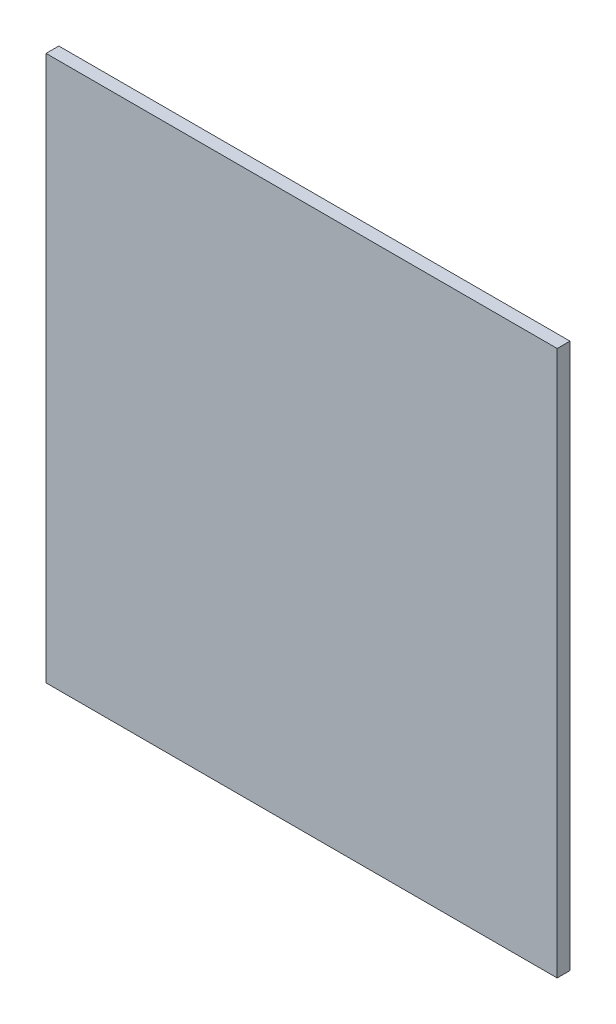
SolidWorks part; units mm, degrees
ref_plane "Alzado" through (0, 0, 0) normal (0, 0, 1) x (1, 0, 0)
ref_plane "Planta" through (0, 0, 0) normal (0, 1, 0) x (1, 0, 0)
ref_plane "Vista lateral" through (0, 0, 0) normal (1, 0, 0) x (0, 0, -1)
sketch "Croquis1" plane through (0, 0, 0) normal (0, 0, 1) x (1, 0, 0)
  line L1 (200, 213.32) -> (-200, 213.32)
  line L2 (200, 213.32) -> (200, -213.32)
  line L3 (200, -213.32) -> (-200, -213.32)
  line L4 (-200, 213.32) -> (-200, -213.32)
  line L5 (200, 213.32) -> (-200, -213.32) construction
  line L6 (200, -213.32) -> (-200, 213.32) construction
  point P0 (0, 0)
  dimension "D1" = 400
  dimension "D2" = 426.64
extrude "Saliente-Extruir1" add sketch "Croquis1" along normal blind 10
sketch "Croquis2" plane through (0, 0, 0) normal (0, 0, -1) x (-1, 0, 0)
  line L0 (-200, -213.32) -> (-200, -183.32)
  line L1 (-200, -213.32) -> (-200, 213.32) construction
  line L2 (-200, -183.32) -> (-170, -183.32)
  line L3 (-200, 213.32) -> (-170, 213.32)
  line L4 (-200, 213.32) -> (200, 213.32) construction
  line L5 (-170, 213.32) -> (-170, 183.32)
  line L6 (200, 213.32) -> (170, 213.32)
  line L7 (170, 213.32) -> (170, 183.32)
  line L8 (200, -213.32) -> (170, -213.32)
  line L9 (200, -213.32) -> (-200, -213.32) construction
  line L10 (170, -213.32) -> (170, -183.32)
  line L12 (-170, 170.6183) -> (-159, 176.9691)
  line L13 (-159, 176.9691) -> (-159, 189.6709)
  line L14 (-159, 189.6709) -> (-170, 196.0217)
  line L15 (-170, 196.0217) -> (-181, 189.6709)
  line L16 (-181, 189.6709) -> (-181, 176.9691)
  line L17 (-181, 176.9691) -> (-170, 170.6183)
  line L18 (-170, -170.6183) -> (-181, -176.9691)
  line L19 (-181, -176.9691) -> (-181, -189.6709)
  line L20 (-181, -189.6709) -> (-170, -196.0217)
  line L21 (-170, -196.0217) -> (-159, -189.6709)
  line L22 (-159, -189.6709) -> (-159, -176.9691)
  line L23 (-159, -176.9691) -> (-170, -170.6183)
  line L24 (170, 170.6183) -> (181, 176.9691)
  line L25 (181, 176.9691) -> (181, 189.6709)
  line L26 (181, 189.6709) -> (170, 196.0217)
  line L27 (170, 196.0217) -> (159, 189.6709)
  line L28 (159, 189.6709) -> (159, 176.9691)
  line L29 (159, 176.9691) -> (170, 170.6183)
  line L30 (170, -170.6183) -> (159, -176.9691)
  line L31 (159, -176.9691) -> (159, -189.6709)
  line L32 (159, -189.6709) -> (170, -196.0217)
  line L33 (170, -196.0217) -> (181, -189.6709)
  line L34 (181, -189.6709) -> (181, -176.9691)
  line L35 (181, -176.9691) -> (170, -170.6183)
  circle A0 centre (-170, 183.32) radius 11 construction
  circle A1 centre (-170, -183.32) radius 11 construction
  circle A2 centre (170, 183.32) radius 11 construction
  circle A3 centre (170, -183.32) radius 11 construction
  dimension "D9" = 22
  dimension "D10" = 22
  dimension "D11" = 22
  dimension "D12" = 22
  dimension "D1" = 30
  dimension "D2" = 30
  dimension "D3" = 30
  dimension "D4" = 30
  dimension "D5" = 30
  dimension "D6" = 30
  dimension "D7" = 30
  dimension "D8" = 30
extrude "Saliente-Extruir2" add sketch "Croquis2" along normal blind 10
